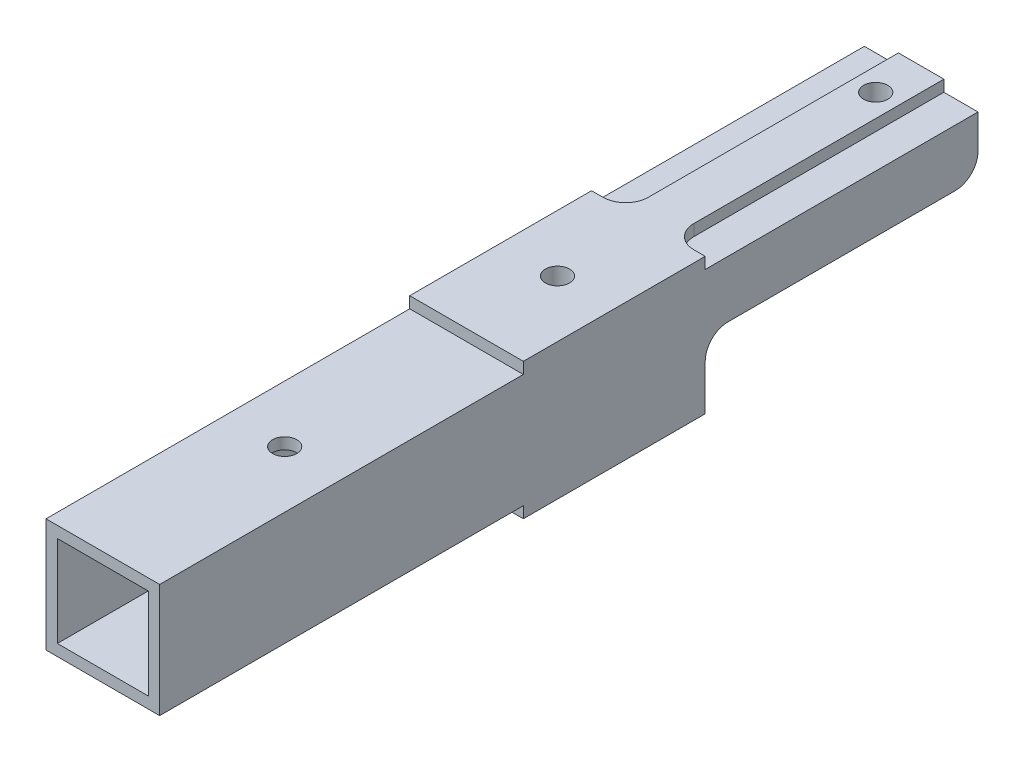
SolidWorks part; units mm, degrees
material "6061-T6 (SS)"
ref_plane "Front" through (0, 0, 0) normal (0, 0, 1) x (1, 0, 0)
ref_plane "Top" through (0, 0, 0) normal (0, 1, 0) x (1, 0, 0)
ref_plane "Right" through (0, 0, 0) normal (1, 0, 0) x (0, 0, -1)
sketch "Sketch1" plane through (0, 0, 0) normal (0, 0, 1) x (1, 0, 0)
  line L0 (-12.7, 12.7) -> (12.7, 12.7)
  line L1 (-19.05, -19.05) -> (19.05, -19.05)
  line L2 (-19.05, -19.05) -> (-19.05, 19.05)
  line L3 (-19.05, 19.05) -> (19.05, 19.05)
  line L4 (19.05, -19.05) -> (19.05, 19.05)
  line L5 (-19.05, -19.05) -> (19.05, 19.05) construction
  line L6 (-19.05, 19.05) -> (19.05, -19.05) construction
  line L7 (12.7, -12.7) -> (12.7, 12.7)
  line L8 (-12.7, -12.7) -> (12.7, -12.7)
  line L9 (-12.7, -12.7) -> (-12.7, 12.7)
  point P0 (0, 0)
  dimension "D1" = 38.1
  dimension "D2" = 6.35
extrude "Extrude1" add sketch "Sketch1" against normal blind 228.6
hole_wizard "1/4 Clearance Hole1" positions "Sketch3" profile "Sketch2" hole size "1/4" standard "Ansi Inch" end condition through all
sketch "Sketch3" plane through (0, 19.05, 0) normal (0, 1, 0) x (-1, 0, 0)
  line L1 (-19.05, -50.8) -> (19.05, -50.8) construction
  line L2 (-19.05, -228.6) -> (-19.05, 0) construction
  line L3 (19.05, -228.6) -> (19.05, 0) construction
  line L5 (-19.05, -215.9) -> (19.05, -215.9) construction
  line L7 (-19.05, -228.6) -> (19.05, -228.6) construction
  line L8 (-19.05, 0) -> (19.05, 0) construction
  line L9 (-19.05, -127) -> (19.05, -127) construction
  point P0 (0, -215.9)
  point P1 (0, -50.8)
  point P24 (0, -127)
  dimension "D1" = 12.7
  dimension "D2" = 50.8
  dimension "D3" = 101.6
sketch "Sketch2" plane through (0, 19.05, -215.9) normal (1, 0, 0) x (0, 0, 1)
  line L0 (0, 0) -> (0, 38.1)
  line L1 (0, 38.1) -> (3.3782, 38.1)
  line L2 (3.3782, 38.1) -> (3.3782, 0)
  line L5 (3.3782, 0) -> (0, 0)
  line L11 (0, -6.35) -> (0, 107.95) construction
  dimension "Thru Hole Dia." = 6.7564
  dimension "Thru Hole Depth" = 38.1
sketch "Sketch4" plane through (0, 19.05, 0) normal (0, 1, 0) x (1, 0, 0)
  line L0 (-19.05, 228.6) -> (-19.05, 0) construction
  line L1 (-6.35, 215.9) -> (6.35, 215.9) construction
  line L2 (-19.05, 228.6) -> (-6.35, 228.6)
  line L3 (-19.05, 228.6) -> (-19.05, 152.4)
  line L4 (-19.05, 152.4) -> (-6.35, 152.4)
  line L5 (19.05, 228.6) -> (19.05, 0) construction
  line L7 (-19.05, 101.6) -> (19.05, 101.6)
  line L8 (-19.05, 101.6) -> (-19.05, 0)
  line L9 (-19.05, 0) -> (19.05, 0)
  line L10 (19.05, 101.6) -> (19.05, 0)
  line L11 (0, 127) -> (19.05, 127) construction
  line L14 (-6.35, 228.6) -> (-6.35, 152.4)
  line L15 (19.05, 228.6) -> (6.35, 228.6)
  line L16 (19.05, 228.6) -> (19.05, 152.4)
  line L17 (19.05, 152.4) -> (6.35, 152.4)
  line L18 (6.35, 228.6) -> (6.35, 152.4)
  line L19 (19.05, 0) -> (-19.05, 0) construction
  circle A0 centre (0, 215.9) radius 3.3782 construction
  point P25 (0, 215.9)
  dimension "D1" = 25.4
  dimension "D2" = 12.7
  dimension "D4" = 25.4
extrude "Extrude2" cut sketch "Sketch4" against normal blind 3.175
mirror "Mirror1" about plane through (0, 0, 0) normal (0, 1, 0) of "Extrude2"
sketch "Sketch5" plane through (19.05, 0, 0) normal (1, 0, 0) x (0, 0, -1)
  line L0 (228.6, -15.875) -> (228.6, 15.875) construction
  line L1 (0, 19.05) -> (228.6, 19.05)
  line L2 (0, 19.05) -> (0, -19.05)
  line L3 (0, -19.05) -> (228.6, -19.05)
  line L4 (228.6, 19.05) -> (228.6, -19.05)
  line L5 (152.4, -19.05) -> (101.6, -19.05) construction
  line L6 (0, -15.875) -> (0, 15.875) construction
  line L7 (152.4, 19.05) -> (101.6, 19.05) construction
extrude "Extrude3" cut sketch "Sketch5" against normal blind 3.175
mirror "Mirror2" about plane through (0, 0, 0) normal (1, 0, 0) of "Extrude3"
fillet "Fillet2" radius 6.35 2 edges at (-6.35, 17.4625, -152.4) (6.35, 17.4625, -152.4)
sketch "Sketch8" plane through (15.875, 0, 0) normal (1, 0, 0) x (0, 0, -1)
  line L0 (228.6, -15.875) -> (228.6, 15.875) construction
  line L1 (228.6, 0) -> (152.4, 0)
  line L2 (228.6, 0) -> (228.6, -19.05)
  line L3 (228.6, -19.05) -> (152.4, -19.05)
  line L4 (152.4, 0) -> (152.4, -19.05)
extrude "Extrude6" cut sketch "Sketch8" against normal through all
fillet "Fillet3" radius 6.35 2 edges at (-14.2875, 0, -152.4) (14.2875, 0, -152.4)
fillet "Fillet4" radius 6.35 2 edges at (-14.2875, 0, -228.6) (14.2875, 0, -228.6)
